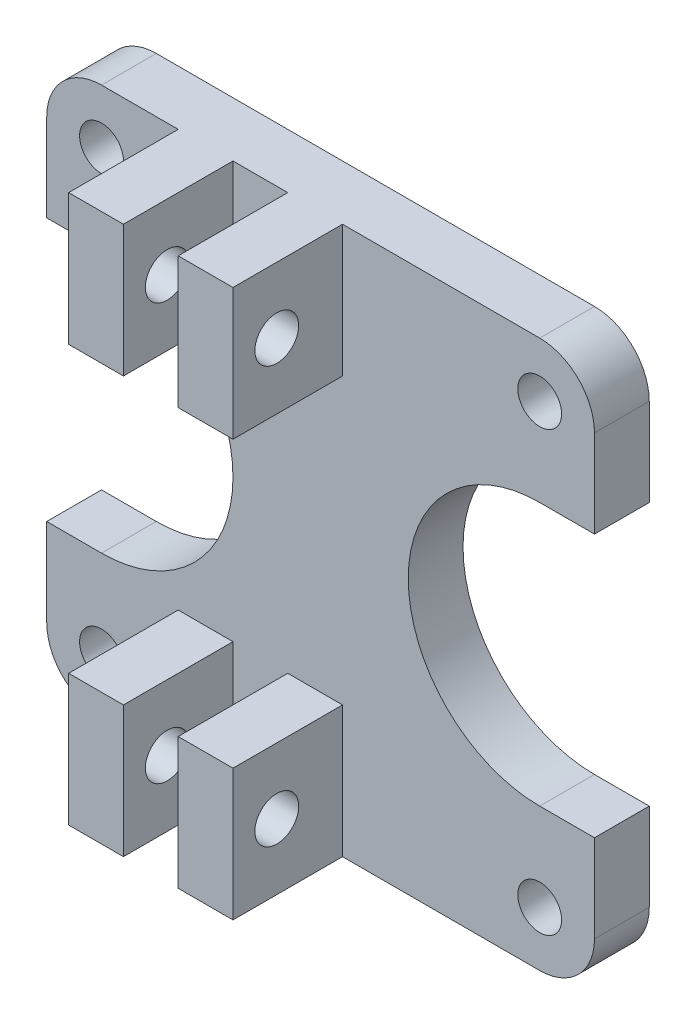
SolidWorks part; units mm, degrees
ref_plane "前视基准面" through (0, 0, 0) normal (0, 0, 1) x (1, 0, 0)
ref_plane "上视基准面" through (0, 0, 0) normal (0, 1, 0) x (1, 0, 0)
ref_plane "右视基准面" through (0, 0, 0) normal (1, 0, 0) x (0, 0, -1)
sketch "草图1" plane through (0, 0, 0) normal (0, 0, 1) x (1, 0, 0)
  line L0 (-25, -25) -> (25, -25)
  line L1 (-25, 25) -> (25, 25)
  line L2 (-25, 25) -> (-25, 12)
  line L4 (25, 25) -> (25, 12)
  line L9 (-20, 12) -> (-25, 12)
  line L10 (-20, -12) -> (-25, -12)
  line L11 (-25, -12) -> (-25, -25)
  line L17 (0, 0) -> (47.5205, 0) construction
  line L18 (0, 0) -> (0, 34.7317) construction
  line L19 (20, -12) -> (25, -12)
  line L20 (20, 12) -> (25, 12)
  line L21 (25, -12) -> (25, -25)
  circle A0 centre (-20, 20) radius 2
  circle A1 centre (-20, -20) radius 2
  circle A2 centre (20, 20) radius 2
  circle A3 centre (20, -20) radius 2
  arc A4 (-20, -12) -> (-20, 12) centre (-20, 0) ccw
  arc A6 (20, -12) -> (20, 12) centre (20, 0) cw
  point P8 (0, 25)
  dimension "D9" = 4
  dimension "D11" = 24
  dimension "D1" = 50
  dimension "D6" = 40
  dimension "D8" = 5
  dimension "D10" = 5
  dimension "D12" = 5
  dimension "D17" = 20
extrude "凸台-拉伸1" add sketch "草图1" along normal mid plane 5
fillet "圆角1" radius 5 4 edges at (25, 25, 0) (-25, 25, 0) (25, -25, 0) (-25, -25, 0)
sketch "草图2" plane through (0, 0, 2.5) normal (0, 0, 1) x (1, 0, 0)
  line L0 (20, 25) -> (-20, 25) construction
  line L1 (-13, 25) -> (-8, 25)
  line L2 (-13, 25) -> (-13, 13)
  line L3 (-13, 13) -> (-8, 13)
  line L4 (-8, 25) -> (-8, 13)
  line L5 (-8, 0) -> (8, 0) construction
  line L6 (0, 25) -> (0, -25) construction
  line L7 (-20, -25) -> (20, -25) construction
  line L8 (-25, 20) -> (-25, 12) construction
  line L9 (2, -25) -> (2, -13)
  line L10 (-3, 25) -> (2, 25)
  line L11 (-3, 25) -> (-3, 13)
  line L12 (-3, 13) -> (2, 13)
  line L13 (2, 25) -> (2, 13)
  line L14 (-3, -13) -> (2, -13)
  line L15 (-3, -25) -> (-3, -13)
  line L16 (-3, -25) -> (2, -25)
  line L17 (-8, -25) -> (-8, -13)
  line L18 (-13, -13) -> (-8, -13)
  line L19 (-13, -25) -> (-13, -13)
  line L20 (-13, -25) -> (-8, -25)
  arc A0 (-20, -12) -> (-20, 12) centre (-20, 0) ccw construction
  arc A1 (20, 12) -> (20, -12) centre (20, 0) ccw construction
  dimension "D1" = 17
  dimension "D2" = 5
  dimension "D3" = 12
  dimension "D4" = 5
  dimension "D5" = 5
extrude "凸台-拉伸2" add sketch "草图2" along normal blind 10
sketch "草图3" plane through (-13, 0, 0) normal (-1, 0, 0) x (0, 0, 1)
  line L0 (12.5, 25) -> (12.5, 13) construction
  line L1 (12.5, -13) -> (12.5, -25) construction
  circle A0 centre (8.5, 19) radius 2
  circle A1 centre (8.5, -19) radius 2
  point P6 (0, 0)
  point P7 (12.5, 19)
  point P10 (12.5, -19)
  point P11 (0, 0)
  dimension "D1" = 4
  dimension "D2" = 4
extrude "切除-拉伸1" cut sketch "草图3" against normal through all
